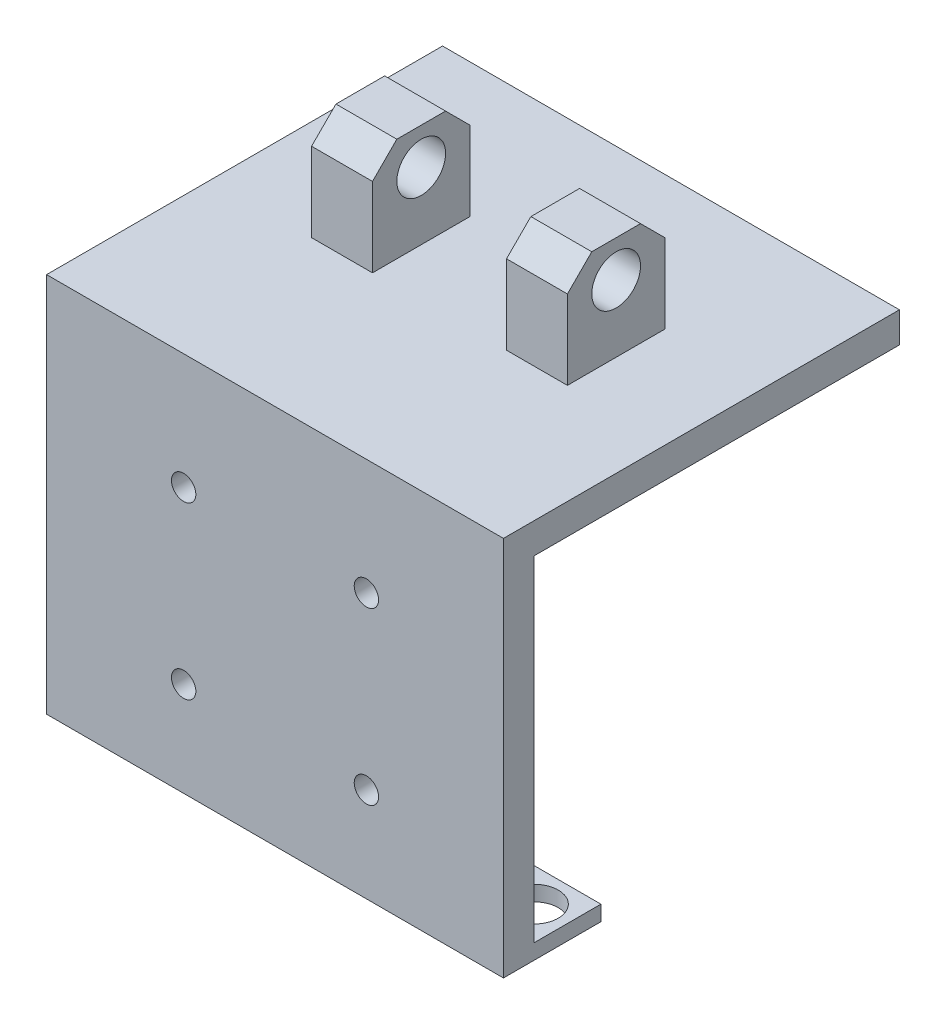
SolidWorks part; units mm, degrees
ref_plane "前视基准面" through (0, 0, 0) normal (0, 0, 1) x (1, 0, 0)
ref_plane "上视基准面" through (0, 0, 0) normal (0, 1, 0) x (1, 0, 0)
ref_plane "右视基准面" through (0, 0, 0) normal (1, 0, 0) x (0, 0, -1)
sketch "草图1" plane through (0, 0, 0) normal (0, 1, 0) x (1, 0, 0)
  line L0 (-7.1888, -6.5668) -> (-7.1888, 3.9332) construction
  line L1 (-12.6888, 9.4332) -> (62.3112, 9.4332)
  line L2 (-12.6888, 9.4332) -> (-12.6888, -6.5668)
  line L3 (-12.6888, -6.5668) -> (62.3112, -6.5668)
  line L4 (62.3112, 9.4332) -> (62.3112, -6.5668)
  line L5 (-7.1888, 3.9332) -> (-12.6888, 3.9332) construction
  line L6 (56.8112, -6.5668) -> (56.8112, 3.9332) construction
  line L7 (56.8112, 3.9332) -> (62.3112, 3.9332) construction
  circle A0 centre (-7.1888, 3.9332) radius 4
  circle A1 centre (56.8112, 3.9332) radius 4
  dimension "D5" = 8
  dimension "D8" = 8
  dimension "D1" = 16
  dimension "D2" = 75
  dimension "D3" = 5.5
  dimension "D4" = 10.5
  dimension "D6" = 5.5
  dimension "D7" = 10.5
extrude "凸台-拉伸1" add sketch "草图1" against normal blind 2.5
sketch "草图3" plane through (0, 0, 0) normal (0, 1, 0) x (1, 0, 0)
  line L1 (-12.6888, -1.5668) -> (62.3112, -1.5668)
  line L2 (-12.6888, -1.5668) -> (-12.6888, -6.5668)
  line L3 (-12.6888, -6.5668) -> (62.3112, -6.5668)
  line L4 (62.3112, -1.5668) -> (62.3112, -6.5668)
  line L5 (-12.6888, -6.5668) -> (62.3112, -6.5668) construction
  point P6 (24.8112, -6.5668)
  point P7 (24.8112, -6.5668)
  dimension "D1" = 5
  dimension "D2" = 75
extrude "凸台-拉伸2" add sketch "草图3" along normal blind 60
sketch "草图4" plane through (0, 0, 1.5668) normal (0, 0, -1) x (-1, 0, 0)
  line L0 (-24.8112, 0) -> (-24.8112, 13) construction
  line L1 (-62.3112, 0) -> (12.6888, 0) construction
  line L2 (-24.8112, 13) -> (-9.8112, 13) construction
  line L3 (-9.8112, 13) -> (-9.8112, 41) construction
  line L4 (-24.8112, 13) -> (-39.8112, 13) construction
  line L5 (-39.8112, 13) -> (-39.8112, 41) construction
  circle A0 centre (-9.8112, 13) radius 2
  circle A1 centre (-9.8112, 41) radius 2
  circle A2 centre (-39.8112, 41) radius 2
  circle A3 centre (-39.8112, 13) radius 2
  dimension "D4" = 4
  dimension "D5" = 4
  dimension "D6" = 4
  dimension "D7" = 4
  dimension "D1" = 13
  dimension "D2" = 15
  dimension "D3" = 28
extrude "切除-拉伸1" cut sketch "草图4" against normal up to next
sketch "草图5" plane through (0, 0, 1.5668) normal (0, 0, -1) x (-1, 0, 0)
  line L0 (-62.3112, 60) -> (12.6888, 60) construction
  line L1 (12.6888, 55) -> (-62.3112, 55)
  line L2 (12.6888, 55) -> (12.6888, 60)
  line L3 (12.6888, 60) -> (-62.3112, 60)
  line L4 (-62.3112, 55) -> (-62.3112, 60)
  point P6 (-24.8112, 60)
  point P7 (-24.8112, 60)
  dimension "D1" = 5
  dimension "D2" = 75
extrude "凸台-拉伸3" add sketch "草图5" along normal blind 60
sketch "草图6" plane through (0, 55, 0) normal (0, -1, 0) x (1, 0, 0)
  line L0 (24.8112, 1.5668) -> (24.8112, -28.4332) construction
  line L1 (62.3112, 1.5668) -> (-12.6888, 1.5668) construction
  line L2 (24.8112, -28.4332) -> (13.8112, -28.4332) construction
  line L3 (24.8112, -28.4332) -> (35.8112, -28.4332) construction
  line L4 (35.8112, -20.4332) -> (35.8112, -36.4332)
  line L5 (35.8112, -20.4332) -> (45.8112, -20.4332)
  line L6 (45.8112, -20.4332) -> (45.8112, -36.4332)
  line L7 (45.8112, -36.4332) -> (35.8112, -36.4332)
  line L9 (13.8112, -20.4332) -> (3.8112, -20.4332)
  line L10 (13.8112, -20.4332) -> (13.8112, -36.4332)
  line L11 (13.8112, -36.4332) -> (3.8112, -36.4332)
  line L12 (3.8112, -20.4332) -> (3.8112, -36.4332)
  point P8 (35.8112, -28.4332)
  point P15 (13.8112, -28.4332)
  dimension "D1" = 11
  dimension "D2" = 11
  dimension "D3" = 30
  dimension "D4" = 16
  dimension "D5" = 10
  dimension "D6" = 10
  dimension "D7" = 16
extrude "凸台-拉伸4" add sketch "草图6" against normal blind 22
sketch "草图7" plane through (45.8112, 0, 0) normal (1, 0, 0) x (0, 0, -1)
  line L0 (28.4332, 77) -> (28.4332, 71) construction
  line L1 (36.4332, 77) -> (20.4332, 77) construction
  circle A0 centre (28.4332, 71) radius 4
  dimension "D1" = 8
  dimension "D2" = 6
extrude "切除-拉伸2" cut sketch "草图7" against normal through all both and the other way through all
chamfer "倒角1" distance 4 angle 45 4 edges at (8.8112, 77, -20.4332) (40.8112, 77, -20.4332) (40.8112, 77, -36.4332) (8.8112, 77, -36.4332)
